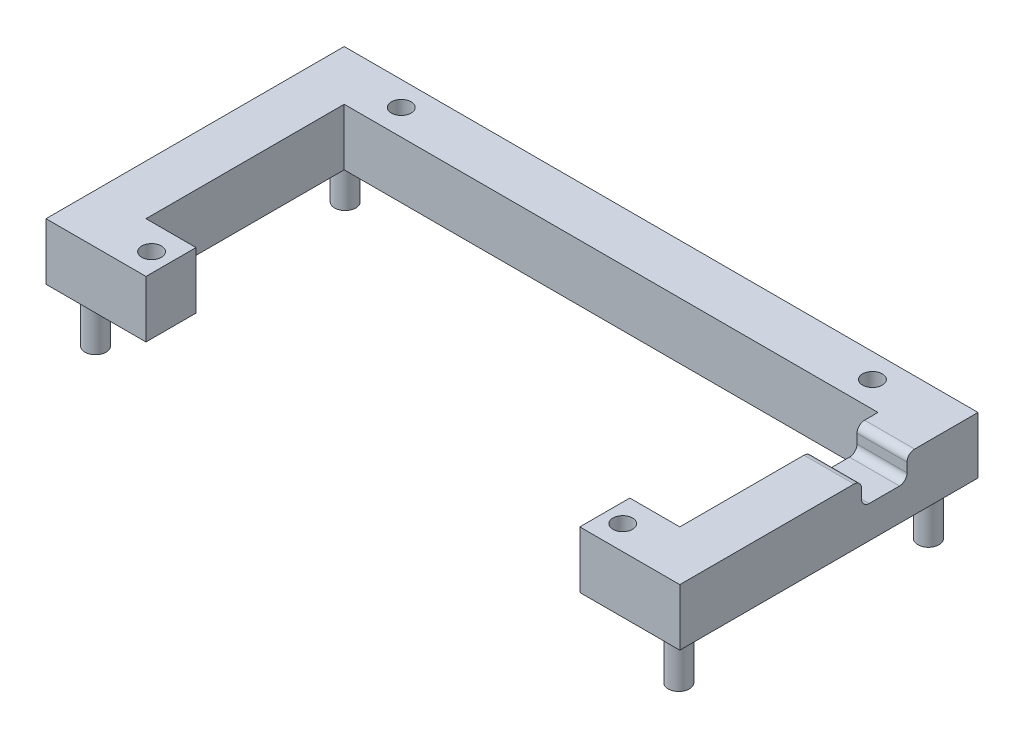
SolidWorks part; units mm, degrees
ref_plane "Front Plane" through (0, 0, 0) normal (0, 0, 1) x (1, 0, 0)
ref_plane "Top Plane" through (0, 0, 0) normal (0, 1, 0) x (1, 0, 0)
ref_plane "Right Plane" through (0, 0, 0) normal (1, 0, 0) x (0, 0, -1)
sketch "Sketch1" plane through (0, 0, 0) normal (0, 1, 0) x (1, 0, 0)
  line L0 (181.4198, 36.9979) -> (75.1552, 36.9979) construction
  line L1 (75.1552, 11.9979) -> (83.5372, 11.9979)
  line L2 (75.1552, 11.9979) -> (75.1552, 61.9979)
  line L3 (75.1552, 61.9979) -> (83.5372, 61.9979)
  line L4 (83.5372, 11.9979) -> (83.5372, 61.9979)
  line L5 (83.5372, 61.9979) -> (91.9192, 61.9979)
  line L6 (83.5372, 61.9979) -> (83.5372, 53.6159)
  line L7 (83.5372, 53.6159) -> (91.9192, 53.6159)
  line L8 (167.7876, 16.0648) -> (186.7138, 16.0648) construction
  line L9 (83.5372, 11.9979) -> (91.9192, 11.9979)
  line L10 (83.5372, 11.9979) -> (83.5372, 20.3799)
  line L11 (83.5372, 20.3799) -> (91.9192, 20.3799)
  line L12 (91.9192, 11.9979) -> (91.9192, 20.3799)
  line L13 (75.1552, 61.9979) -> (181.4198, 61.9979)
  line L17 (181.4198, 61.9979) -> (173.0378, 61.9979)
  line L18 (181.4198, 61.9979) -> (181.4198, 11.9979)
  line L19 (181.4198, 11.9979) -> (173.0378, 11.9979)
  line L20 (173.0378, 61.9979) -> (173.0378, 11.9979)
  line L21 (173.0378, 61.9979) -> (164.6558, 61.9979)
  line L22 (173.0378, 61.9979) -> (173.0378, 53.6159)
  line L23 (173.0378, 53.6159) -> (164.6558, 53.6159)
  line L25 (173.0378, 11.9979) -> (164.6558, 11.9979)
  line L26 (173.0378, 11.9979) -> (173.0378, 20.3799)
  line L27 (173.0378, 20.3799) -> (164.6558, 20.3799)
  line L28 (164.6558, 11.9979) -> (164.6558, 20.3799)
  line L29 (128.2875, 61.9979) -> (128.2875, -9.1774) construction
  line L30 (164.6558, 53.6159) -> (91.9192, 53.6159)
  circle A0 centre (167.7876, 57.931) radius 1.651
  circle A1 centre (167.7876, 16.0648) radius 1.651
  circle A2 centre (88.7875, 16.0648) radius 1.651
  circle A3 centre (88.7875, 57.931) radius 1.651
  point P32 (91.9192, 16.1889)
  point P34 (88.7875, 57.931)
  point P35 (88.7875, 16.0648)
  dimension "D15" = 3.302
  dimension "D16" = 3.1342
  dimension "D6" = 79.0001
  dimension "D1" = 8.382
  dimension "D3" = 50
  dimension "D4" = 8.382
  dimension "D5" = 50
  dimension "D7" = 8.382
  dimension "D8" = 8.382
  dimension "D9" = 8.382
  dimension "D10" = 8.382
  dimension "D11" = 8.382
  dimension "D12" = 8.382
  dimension "D13" = 8.382
  dimension "D14" = 8.382
  dimension "D17" = 3.1317
extrude "Boss-Extrude1" add sketch "Sketch1" along normal blind 9.525
sketch "Sketch2" plane through (181.4198, 0, 0) normal (1, 0, 0) x (0, 0, -1)
  line L0 (61.9979, 9.525) -> (11.9979, 9.525) construction
  line L1 (42.4779, 9.525) -> (50.0979, 9.525)
  line L2 (42.4779, 9.525) -> (42.4779, 5.4254)
  line L3 (42.4779, 5.4254) -> (50.0979, 5.4254)
  line L4 (50.0979, 9.525) -> (50.0979, 5.4254)
  line L5 (11.9979, 9.525) -> (11.9979, 0) construction
  dimension "D1" = 30.48
  dimension "D2" = 7.62
extrude "Cut-Extrude7" cut sketch "Sketch2" against normal blind 8.89 contours L2 L3 L4 L1
fillet "Fillet2" radius 1.27 4 edges at (177.2288, 5.4254, -42.4779) (177.2288, 9.525, -42.4779) (177.2288, 5.4254, -50.0979) (177.2288, 9.525, -50.0979)
sketch "Sketch3" plane through (0, 0, 0) normal (0, -1, 0) x (1, 0, 0)
  circle A0 centre (79.3895, -16.0648) radius 1.778
  circle A1 centre (177.1856, -16.0648) radius 1.778
  circle A2 centre (79.3895, -57.931) radius 1.778
  circle A3 centre (177.1856, -57.931) radius 1.778
extrude "Boss-Extrude3" add sketch "Sketch3" along normal blind 8.89 contours A0 | A2 | A3 | A1
